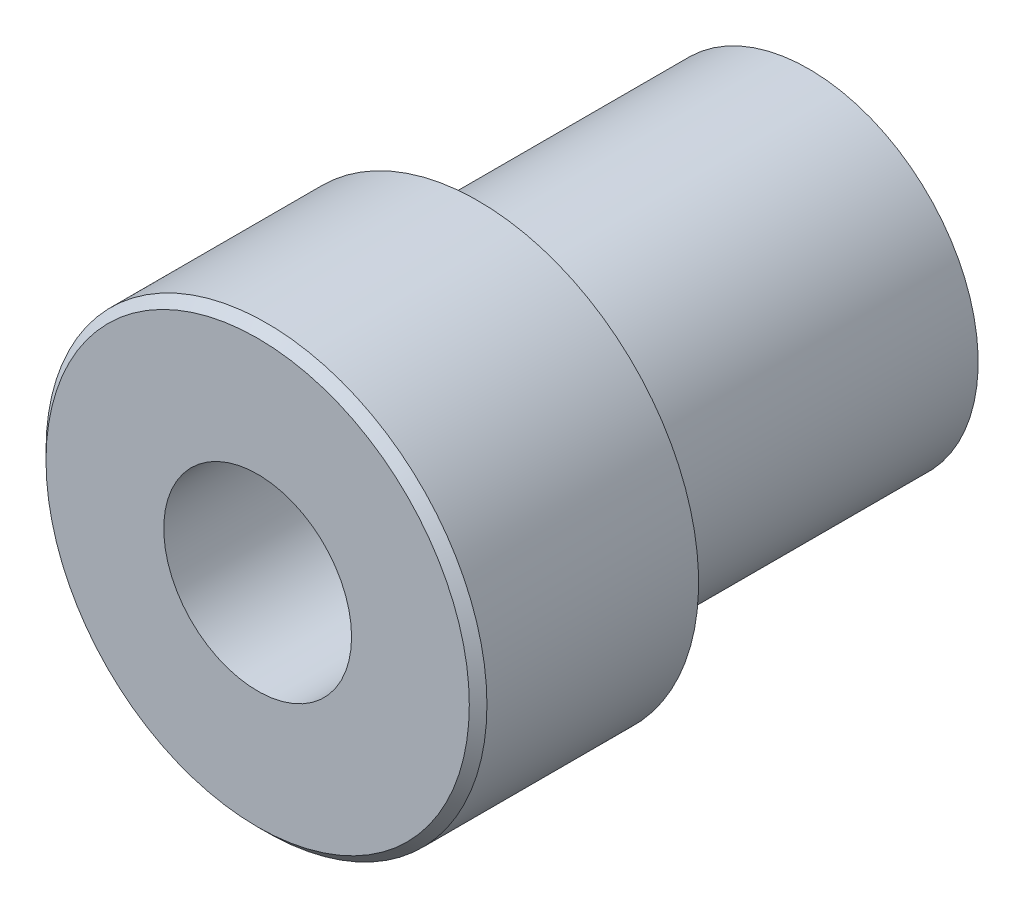
SolidWorks part; units mm, degrees
material "AISI 4130 Steel, annealed at 865C"
ref_plane "Front" through (0, 0, 0) normal (0, 0, 1) x (1, 0, 0)
ref_plane "Top" through (0, 0, 0) normal (0, 1, 0) x (1, 0, 0)
ref_plane "Right" through (0, 0, 0) normal (1, 0, 0) x (0, 0, -1)
sketch "Sketch1" plane through (0, 0, 0) normal (0, 0, 1) x (1, 0, 0)
  circle A0 centre (0, 0) radius 6.35
  dimension "D1" = 12.7
extrude "Boss-Extrude1" add sketch "Sketch1" along normal blind 15.875
chamfer "Chamfer1" distance 0.254 angle 45 1 edges at (6.35, 0, 15.875)
sketch "Sketch2" plane through (0, 0, 0) normal (0, 0, -1) x (-1, 0, 0)
  circle A0 centre (0, 0) radius 4.8768
  circle A1 centre (0, 0) radius 6.35 construction
  dimension "D1" = 1.4732
extrude "Cut-Extrude1" cut sketch "Sketch2" against normal blind 9.525 flip side to cut
hole_wizard "Tap Drill for 3/8-24 Tap1" positions "Sketch5" profile "Sketch6" hole size "3/8-24" standard "ANSI Inch"
sketch "Sketch5" plane through (0, 0, 15.875) normal (0, 0, 1) x (1, 0, 0)
  point P0 (0, 0)
sketch "Sketch6" plane through (0, 0, 15.875) normal (1, 0, 0) x (0, -1, 0)
  line L0 (0, 0) -> (0, 15.875)
  line L1 (0, 15.875) -> (4.2164, 15.875)
  line L2 (4.2164, 15.875) -> (4.2164, 0)
  line L5 (4.2164, 0) -> (0, 0)
  line L11 (0, -6.35) -> (0, 107.95) construction
  dimension "Thru Hole Dia." = 8.4328
  dimension "Thru Hole Depth" = 15.875
hole_wizard "Tap Drill for 5/16-18 Tap1" positions "Sketch7" profile "Sketch8" hole size "5/16-18" standard "ANSI Inch"
sketch "Sketch7" plane through (0, 0, 15.875) normal (0, 0, 1) x (1, 0, 0)
  point P0 (0, 0)
sketch "Sketch8" plane through (0, 0, 15.875) normal (1, 0, 0) x (0, -1, 0)
  line L0 (0, 0) -> (0, 15.875)
  line L1 (0, 15.875) -> (3.2639, 15.875)
  line L2 (3.2639, 15.875) -> (3.2639, 0)
  line L5 (3.2639, 0) -> (0, 0)
  line L11 (0, -6.35) -> (0, 107.95) construction
  dimension "Thru Hole Dia." = 6.5278
  dimension "Thru Hole Depth" = 15.875
hole_wizard "Tap Drill for 1/4-28 Tap1" positions "Sketch9" profile "Sketch10" hole size "1/4-28" standard "ANSI Inch" end condition through all
sketch "Sketch9" plane through (0, 0, 15.875) normal (0, 0, 1) x (1, 0, 0)
  point P0 (0, 0)
sketch "Sketch10" plane through (0, 0, 15.875) normal (1, 0, 0) x (0, -1, 0)
  line L0 (0, 0) -> (0, 15.875)
  line L1 (0, 15.875) -> (2.7051, 15.875)
  line L2 (2.7051, 15.875) -> (2.7051, 0)
  line L5 (2.7051, 0) -> (0, 0)
  line L11 (0, -6.35) -> (0, 107.95) construction
  dimension "Thru Hole Dia." = 5.4102
  dimension "Thru Hole Depth" = 15.875
equation "\"Tube Radius\"= 1 / 4in"
equation "\"Wall Thickness\"= 0.058"
equation "\"D1@Sketch1\"= 2 * \"Tube Radius\""
equation "\"D1@Sketch2\" = \"Wall Thickness\""
